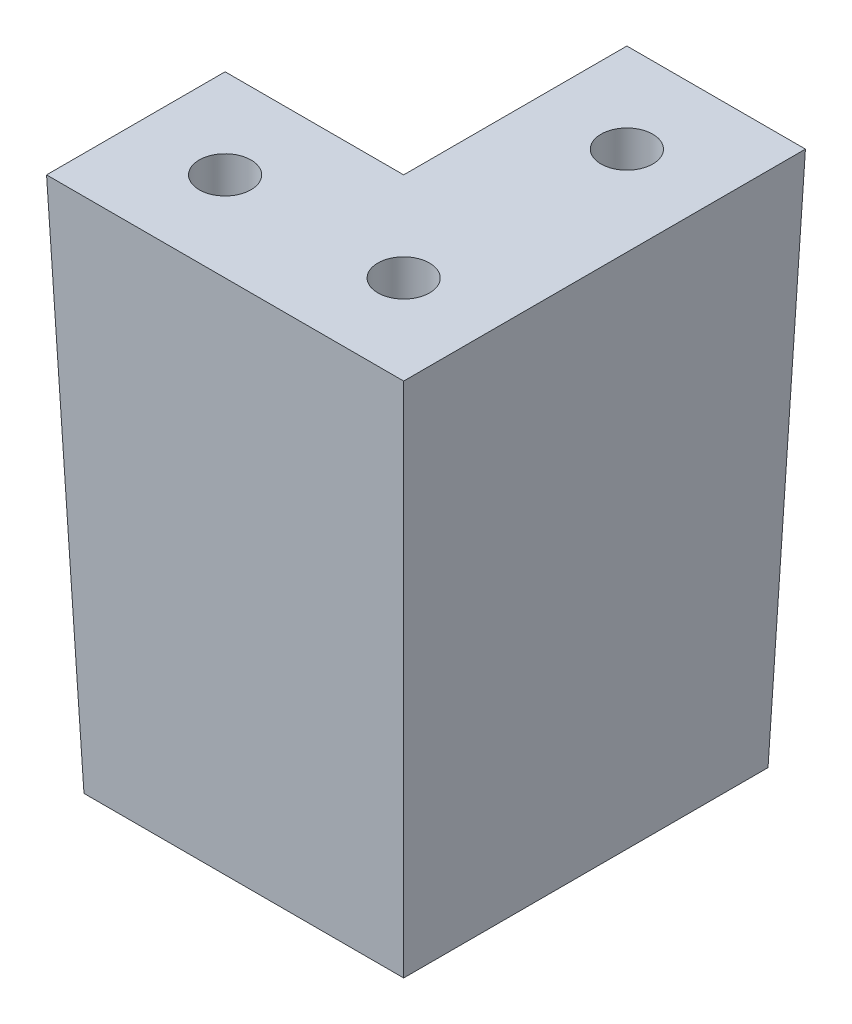
SolidWorks part; units mm, degrees
ref_plane "Front Plane" through (0, 0, 0) normal (0, 0, 1) x (1, 0, 0)
ref_plane "Top Plane" through (0, 0, 0) normal (0, 1, 0) x (1, 0, 0)
ref_plane "Right Plane" through (0, 0, 0) normal (1, 0, 0) x (0, 0, -1)
sketch "Sketch1" plane through (0, 0, 0) normal (0, 1, 0) x (1, 0, 0)
  line L10 (-1000, 10) -> (49000, 10) construction
  line L11 (0, 0) -> (40, 0)
  line L12 (0, 0) -> (0, 20)
  line L13 (20, 45) -> (40, 45)
  line L14 (40, 0) -> (40, 45)
  line L17 (0, 20) -> (20, 20)
  line L18 (20, 45) -> (20, 20)
  line L19 (30, -955) -> (30, 49045) construction
  point P10 (0, 10)
  point P13 (30, 45)
  dimension "D1" = 45
  dimension "D2" = 40
  dimension "D3" = 20
  dimension "D4" = 20
extrude "Boss-Extrude1" add sketch "Sketch1" against normal blind 60 draft 2
hole_wizard "CBORE for M5 SBHCS1" positions "Sketch2" profile "Sketch3" counterbore size "M5" standard "ANSI Metric" end condition through all
sketch "Sketch2" plane through (0, -60, 0) normal (0, -1, 0) x (-1, 0, 0)
  line L4 (201000, 10) -> (-249000, 10) construction
  line L5 (-30, -200955) -> (-30, 249045) construction
  line L6 (0, 0) -> (0, 20) construction
  line L7 (-20, 45) -> (-40, 45) construction
  point P17 (-30, 10)
  point P23 (-10, 10)
  point P25 (-30, 35)
  point P33 (0, 0)
  point P34 (0, 0)
  point P35 (0, 0)
  point P36 (0, 0)
  dimension "D1" = 10
  dimension "D2" = 10
sketch "Sketch3" plane through (30, -60, -10) normal (1, 0, 0) x (0, 0, -1)
  line L0 (0, 0) -> (0, 60)
  line L1 (0, 60) -> (2.9, 60)
  line L3 (2.9, 60) -> (2.9, 55)
  line L4 (2.9, 55) -> (5.75, 55)
  line L5 (5.75, 55) -> (5.75, 0)
  line L7 (5.75, 0) -> (0, 0)
  line L11 (0, -6.35) -> (0, 107.95) construction
  dimension "Thru Hole Dia." = 5.8
  dimension "Thru Hole Depth" = 60
  dimension "C'Bore Dia." = 11.5
  dimension "C'Bore Depth" = 55
